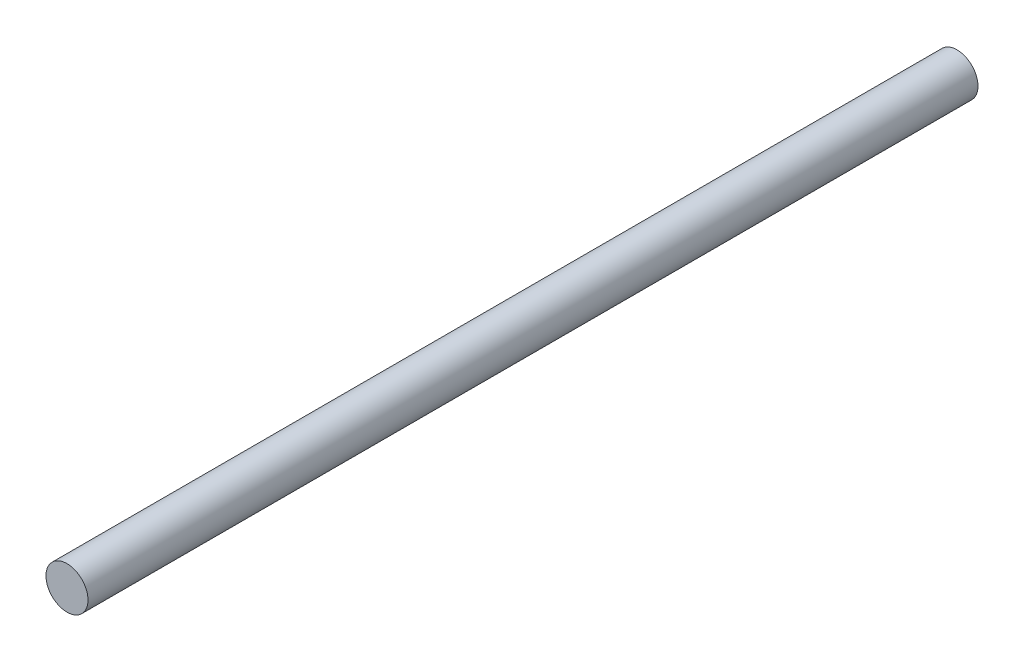
SolidWorks part; units mm, degrees
ref_plane "Alzado" through (0, 0, 0) normal (0, 0, 1) x (1, 0, 0)
ref_plane "Planta" through (0, 0, 0) normal (0, 1, 0) x (1, 0, 0)
ref_plane "Vista lateral" through (0, 0, 0) normal (1, 0, 0) x (0, 0, -1)
sketch "Croquis1" plane through (0, 0, 0) normal (0, 0, 1) x (1, 0, 0)
  circle A0 centre (0, 0) radius 3
  dimension "D1" = 6
extrude "Saliente-Extruir1" add sketch "Croquis1" along normal mid plane 127
